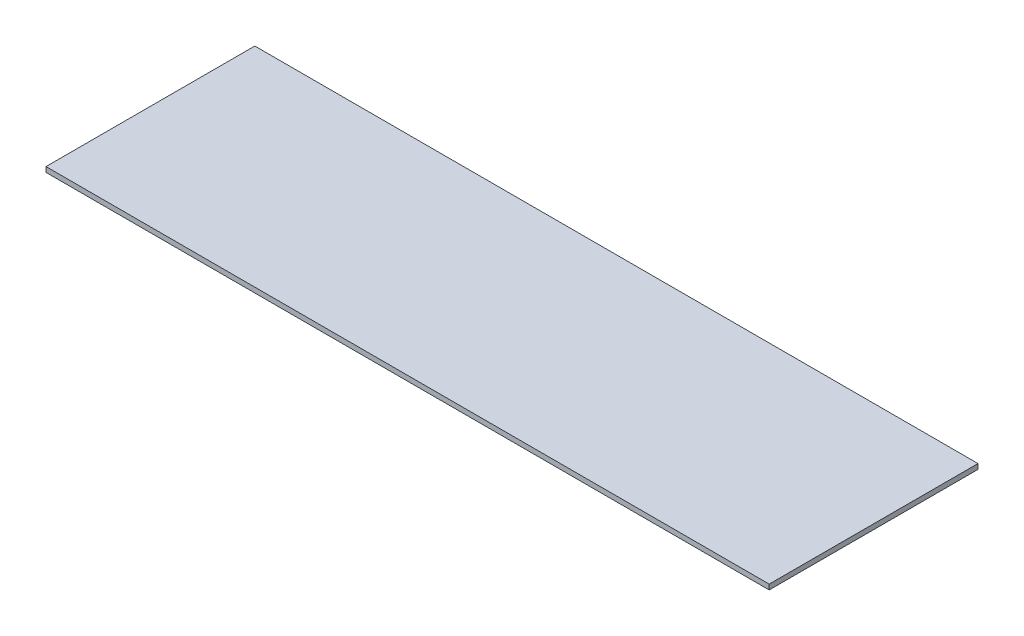
SolidWorks part; units mm, degrees
ref_plane "Front Plane" through (0, 0, 0) normal (0, 0, 1) x (1, 0, 0)
ref_plane "Top Plane" through (0, 0, 0) normal (0, 1, 0) x (1, 0, 0)
ref_plane "Right Plane" through (0, 0, 0) normal (1, 0, 0) x (0, 0, -1)
sketch "Sketch1" plane through (0, 0, 0) normal (0, 1, 0) x (1, 0, 0)
  line L1 (-72.8229, 90.5465) -> (378.0271, 90.5465)
  line L2 (-72.8229, 90.5465) -> (-72.8229, -39.6285)
  line L3 (-72.8229, -39.6285) -> (378.0271, -39.6285)
  line L4 (378.0271, 90.5465) -> (378.0271, -39.6285)
  dimension "D1" = 450.85
  dimension "D2" = 130.175
extrude "Boss-Extrude1" add sketch "Sketch1" against normal blind 3.175
